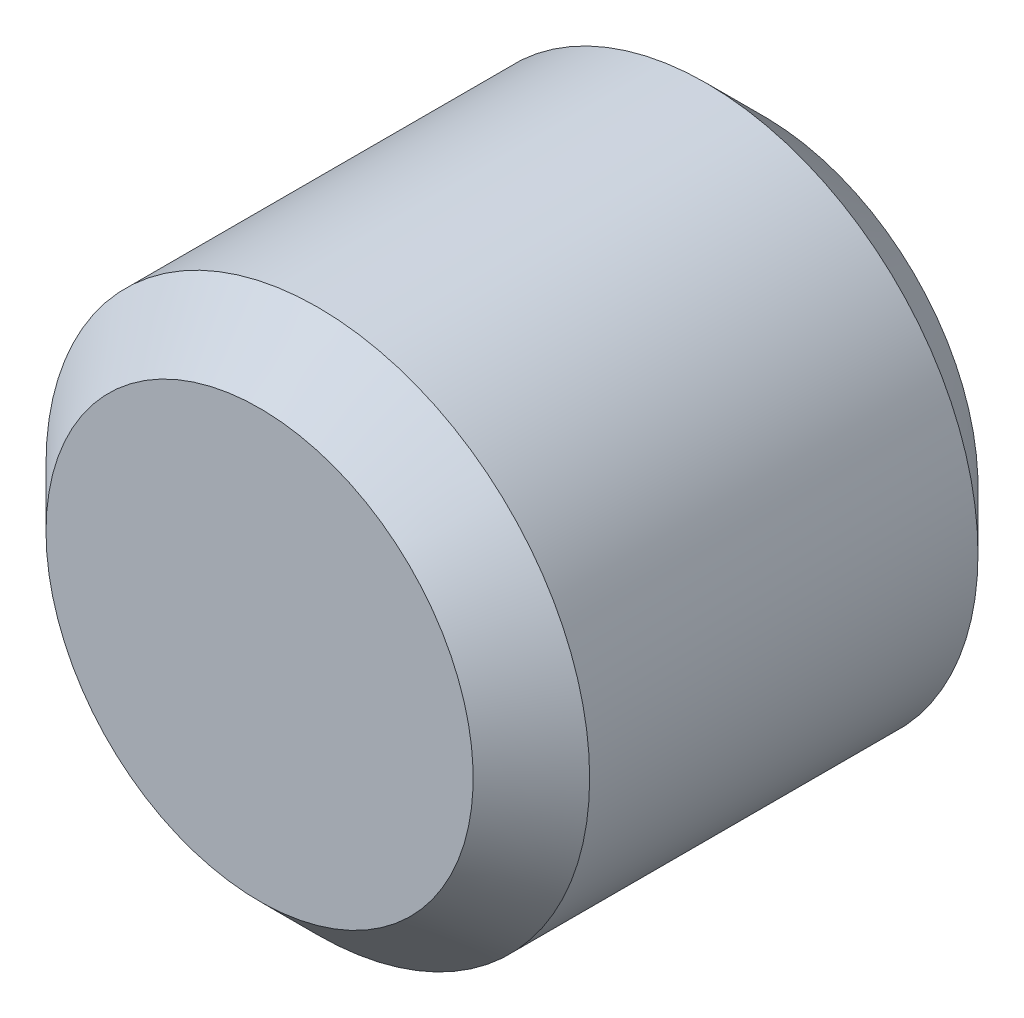
SolidWorks part; units mm, degrees
ref_plane "Front Plane" through (0, 0, 0) normal (0, 0, 1) x (1, 0, 0)
ref_plane "Top Plane" through (0, 0, 0) normal (0, 1, 0) x (1, 0, 0)
ref_plane "Right Plane" through (0, 0, 0) normal (1, 0, 0) x (0, 0, -1)
sketch "Sketch1" plane through (0, 0, 0) normal (0, 1, 0) x (1, 0, 0)
  line L0 (0, 0) -> (-14, 0)
  line L1 (-14, 0) -> (-14, 26)
  line L2 (-14, 26) -> (-1.5, 26)
  line L3 (-1.5, 26) -> (-1.5, 29.2)
  line L4 (-1.5, 29.2) -> (0, 29.2)
  line L5 (0, 29.2) -> (0, 0)
  point P3 (-1.5, 32.2423)
  dimension "D1" = 1.5
  dimension "D2" = 14
  dimension "D3" = 26
  dimension "D4" = 3.2
revolve "Revolve1" add sketch "Sketch1" angle 360 about L5
chamfer "Chamfer1" distance 3 angle 45 2 edges at (-14, 0, 0) (-14, 0, -26)
